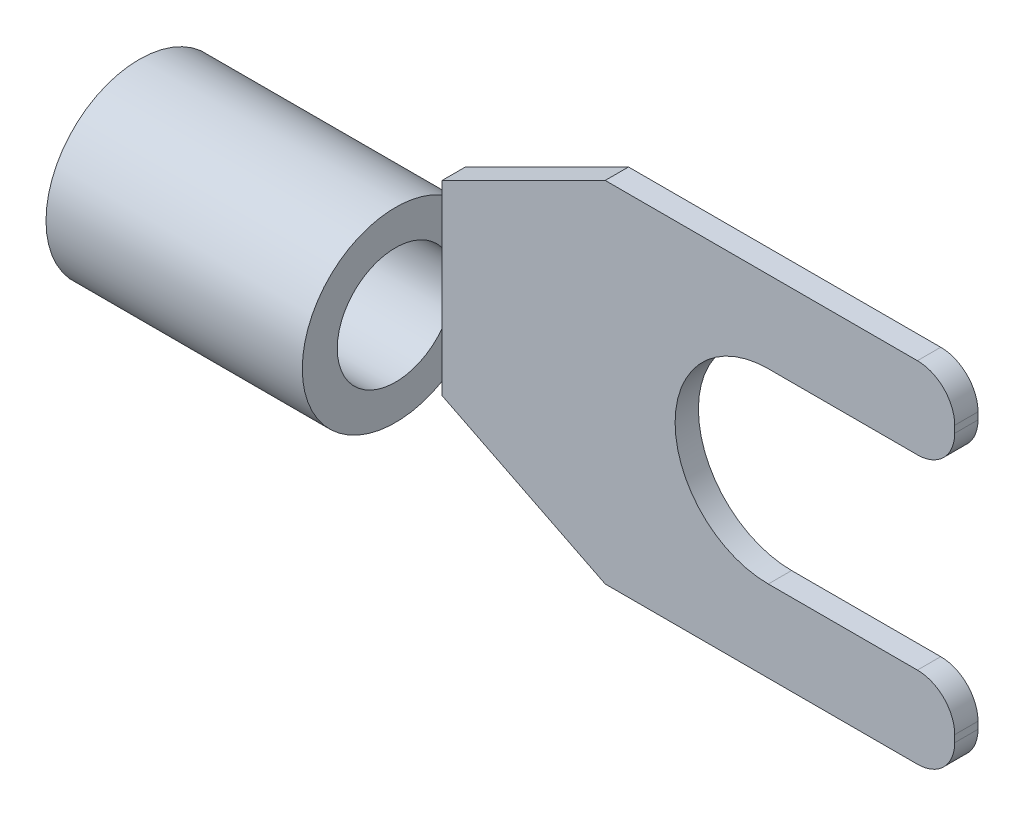
SolidWorks part; units mm, degrees
ref_plane "前视基准面" through (0, 0, 0) normal (0, 0, 1) x (1, 0, 0)
ref_plane "上视基准面" through (0, 0, 0) normal (0, 1, 0) x (1, 0, 0)
ref_plane "右视基准面" through (0, 0, 0) normal (1, 0, 0) x (0, 0, -1)
sketch "草图1" plane through (0, 0, 0) normal (0, 0, 1) x (1, 0, 0)
  line L0 (-59.949, 0) -> (64.78, 0) construction
  line L1 (0, 2) -> (3.2, 2)
  line L2 (-3.5, 3.75) -> (3.2, 3.75)
  line L3 (-34.038, 2.875) -> (50.8649, 2.875) construction
  line L4 (4, -2.95) -> (4, -2.8)
  line L5 (-3.5, -3.75) -> (3.2, -3.75)
  line L6 (0, -2) -> (3.2, -2)
  line L7 (4, 2.95) -> (4, 2.8)
  line L8 (0, -5.9925) -> (0, 5.2415) construction
  line L9 (-3.5, 3.75) -> (-7, 2)
  line L10 (-7, 2) -> (-12.5, 2)
  line L11 (-7, -2) -> (-12.5, -2)
  line L12 (-3.5, -3.75) -> (-7, -2)
  line L13 (-12.5, 2) -> (-12.5, -2)
  arc A0 (4, 2.8) -> (3.2, 2) centre (3.2, 2.8) cw
  arc A1 (4, 2.95) -> (3.2, 3.75) centre (3.2, 2.95) ccw
  arc A2 (4, -2.95) -> (3.2, -3.75) centre (3.2, -2.95) cw
  arc A3 (4, -2.8) -> (3.2, -2) centre (3.2, -2.8) ccw
  arc A4 (0, 2) -> (0, -2) centre (0, 0) ccw
  dimension "D1" = 0.8
  dimension "D5" = 4
  dimension "D2" = 7.5
  dimension "D3" = 4
  dimension "D4" = 7.5
  dimension "D6" = 4
  dimension "D7" = 5.5
  dimension "D8" = 16.5
extrude "凸台-拉伸1" add sketch "草图1" along normal blind 0.5
sketch "草图2" plane through (-12.5, 0, 0) normal (-1, 0, 0) x (0, 0, 1)
  line L0 (-1.5803, 0) -> (2.5411, 0) construction
  line L1 (0, 2) -> (0, -2) construction
  circle A0 centre (1.5, 0) radius 1.25
  circle A1 centre (1.5, 0) radius 2
  dimension "D1" = 4
  dimension "D2" = 1.5
  dimension "D3" = 2.5
extrude "凸台-拉伸2" add sketch "草图2" against normal up to vertex (5.5 mm away)
sketch "草图3" plane through (-12.5, 0, 0) normal (-1, 0, 0) x (0, 0, 1)
  circle A0 centre (1.5, 0) radius 1.25
  arc A1 (0.5, -0.75) -> (0.5, 0.75) centre (1.5, 0) ccw construction
extrude "切除-拉伸1" cut sketch "草图3" against normal up to surface (5.5 mm away) up to face at (-7, 0, 1.8125)
sketch "草图4" plane through (-12.5, 0, 0) normal (-1, 0, 0) x (0, 0, 1)
  circle A0 centre (1.5, 0) radius 2
  arc A1 (0.5, -1.7321) -> (0.5, 1.7321) centre (1.5, 0) ccw construction
  circle A2 centre (1.5, 0) radius 4
  dimension "D1" = 2
extrude "切除-拉伸2" cut sketch "草图4" against normal up to surface (5.5 mm away) up to face at (-7, 0, 1.8125)
